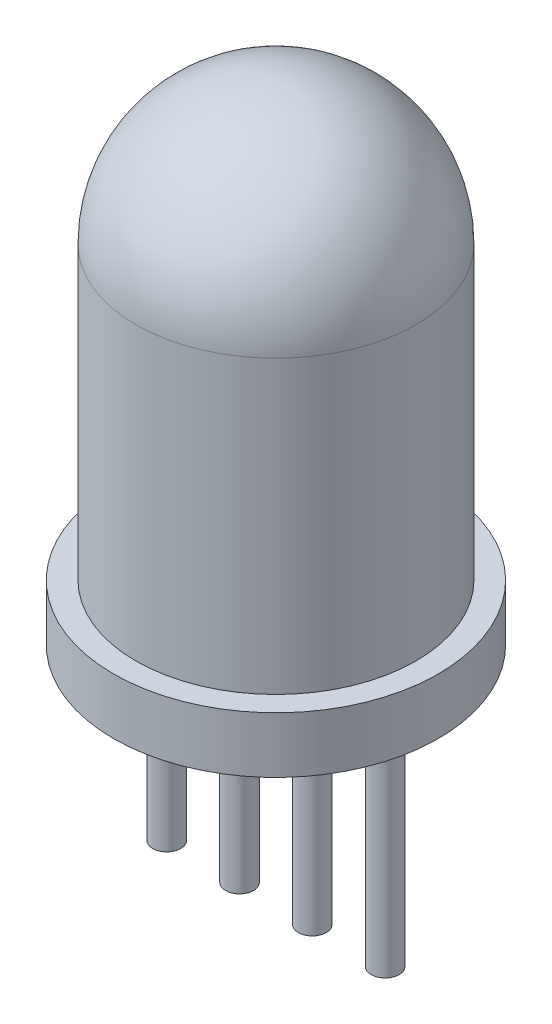
SolidWorks part; units mm, degrees
ref_plane "Front Plane" through (0, 0, 0) normal (0, 0, 1) x (1, 0, 0)
ref_plane "Top Plane" through (0, 0, 0) normal (0, 1, 0) x (1, 0, 0)
ref_plane "Right Plane" through (0, 0, 0) normal (1, 0, 0) x (0, 0, -1)
sketch "Sketch1" plane through (0, 0, 0) normal (1, 0, 0) x (0, 0, -1)
  line L0 (0, 16.4776) -> (0, -16.4788) construction
  line L1 (-2.5, 6.2) -> (-2.5, 1)
  line L2 (-2.5, 1) -> (-2.9, 1)
  line L3 (-2.9, 1) -> (-2.9, 0)
  line L4 (-2.9, 0) -> (0, 0)
  line L5 (0, 8.7) -> (1.4623, 8.7) construction
  line L6 (0, 8.7) -> (0, 0)
  arc A0 (-2.5, 6.2) -> (0, 8.7) centre (0, 6.2) cw
  dimension "D1" = 5
  dimension "D2" = 5.8
  dimension "D3" = 8.7
  dimension "D4" = 1
revolve "Revolve1" add sketch "Sketch1" angle 360 about L0
sketch "Sketch2" plane through (0, 0, 0) normal (0, -1, 0) x (1, 0, 0)
  line L0 (-2.9, 0) -> (2.9, 0) construction
  line L1 (0, 2.9) -> (0, -2.9) construction
  circle A0 centre (0, 0) radius 2.9 construction
  circle A1 centre (-1.95, 0) radius 0.25
  circle A2 centre (-0.65, 0) radius 0.25
  circle A3 centre (0.65, 0) radius 0.25
  circle A4 centre (1.95, 0) radius 0.25
  dimension "D1" = 1.3
  dimension "D3" = 0.5
  dimension "D2" = 1.3
extrude "Boss-Extrude1" add sketch "Sketch2" along normal blind 4
